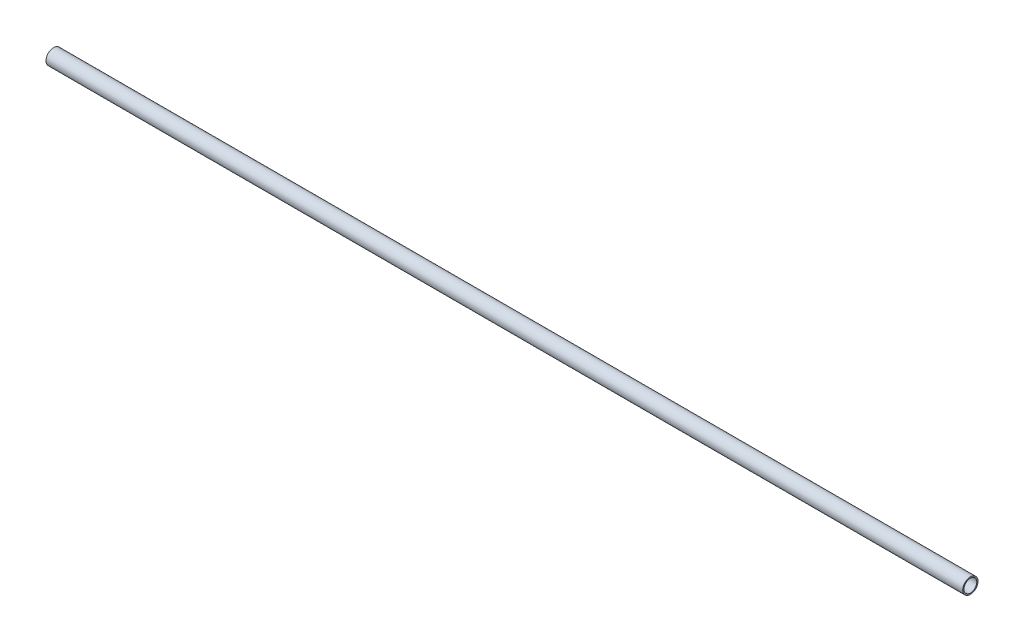
SolidWorks part; units mm, degrees
ref_plane "Alzado" through (0, 0, 0) normal (0, 0, 1) x (1, 0, 0)
ref_plane "Planta" through (0, 0, 0) normal (0, 1, 0) x (1, 0, 0)
ref_plane "Vista lateral" through (0, 0, 0) normal (1, 0, 0) x (0, 0, -1)
sketch "Croquis1" plane through (0, 0, 0) normal (1, 0, 0) x (0, 0, -1)
  circle A0 centre (0, 0) radius 12.5
  circle A1 centre (0, 0) radius 10.5
  dimension "D1" = 25
  dimension "D2" = 2
extrude "Saliente-Extruir1" add sketch "Croquis1" along normal blind 1500
